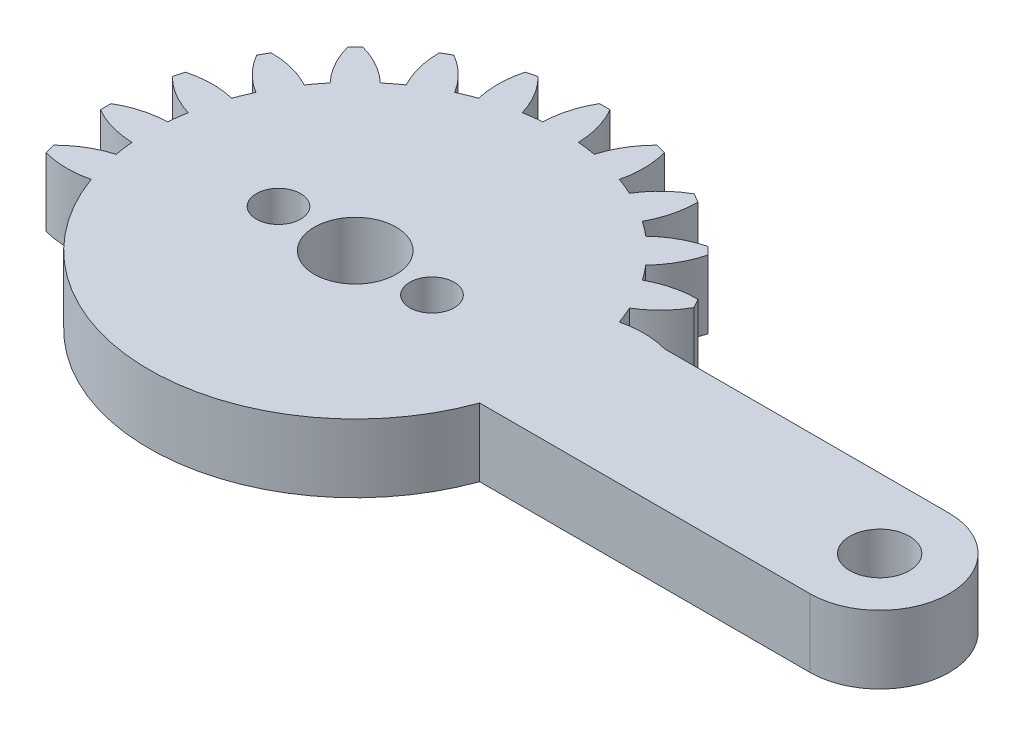
SolidWorks part; units mm, degrees
ref_plane "前视基准面" through (0, 0, 0) normal (0, 0, 1) x (1, 0, 0)
ref_plane "上视基准面" through (0, 0, 0) normal (0, 1, 0) x (1, 0, 0)
ref_plane "右视基准面" through (0, 0, 0) normal (1, 0, 0) x (0, 0, -1)
sketch "草图2" plane through (0, 0, 0) normal (0, 1, 0) x (1, 0, 0)
  line L0 (0, 0) -> (0, 14.63) construction
  line L1 (0, 0) -> (30.75, 0) construction
  line L2 (11.3789, 4.0851) -> (30.75, 4.0851)
  line L3 (30.75, -4.0851) -> (11.3789, -4.0851)
  circle A0 centre (0, 0) radius 14.63
  circle A1 centre (0, 0) radius 12.09
  circle A2 centre (0, 0) radius 1.75
  arc A3 (0.31, 14.6267) -> (1.04, 12.0452) centre (-4.3584, 11.9126) cw
  arc A4 (-0.31, 14.6267) -> (-1.04, 12.0452) centre (4.3584, 11.9126) ccw
  arc A5 (4.0851, 14.0481) -> (4.1221, 11.3656) centre (-1.1267, 12.6347) cw
  arc A6 (3.4862, 14.2086) -> (2.113, 11.9039) centre (7.2931, 10.3787) ccw
  circle A7 centre (0, 0) radius 12.09
  arc A8 (7.5818, 12.5121) -> (6.9233, 9.9114) centre (2.1819, 12.4958) cw
  arc A9 (7.0449, 12.8221) -> (5.1219, 10.9514) centre (9.7308, 8.1374) ccw
  circle A10 centre (0, 0) radius 12.09
  arc A11 (10.5619, 10.1234) -> (9.2526, 7.7818) centre (5.3417, 11.5053) cw
  arc A12 (10.1234, 10.5619) -> (7.7818, 9.2526) centre (11.5053, 5.3417) ccw
  circle A13 centre (0, 0) radius 12.09
  arc A14 (12.8221, 7.0449) -> (10.9514, 5.1219) centre (8.1374, 9.7308) cw
  arc A15 (12.5121, 7.5818) -> (9.9114, 6.9233) centre (12.4958, 2.1819) ccw
  circle A16 centre (0, 0) radius 12.09
  arc A17 (14.2086, 3.4862) -> (11.9039, 2.113) centre (10.3787, 7.2931) cw
  arc A18 (14.0481, 4.0851) -> (11.3656, 4.1221) centre (12.6347, -1.1267) ccw
  circle A19 centre (0, 0) radius 12.09
  arc A20 (14.6267, -0.31) -> (12.0452, -1.04) centre (11.9126, 4.3584) cw
  arc A21 (14.6267, 0.31) -> (12.0452, 1.04) centre (11.9126, -4.3584) ccw
  circle A22 centre (0, 0) radius 12.09
  arc A23 (14.0481, -4.0851) -> (11.3656, -4.1221) centre (12.6347, 1.1267) cw
  arc A24 (14.2086, -3.4862) -> (11.9039, -2.113) centre (10.3787, -7.2931) ccw
  circle A25 centre (0, 0) radius 12.09
  arc A26 (12.5121, -7.5818) -> (9.9114, -6.9233) centre (12.4958, -2.1819) cw
  arc A27 (12.8221, -7.0449) -> (10.9514, -5.1219) centre (8.1374, -9.7308) ccw
  circle A28 centre (0, 0) radius 12.09
  arc A29 (10.1234, -10.5619) -> (7.7818, -9.2526) centre (11.5053, -5.3417) cw
  arc A30 (10.5619, -10.1234) -> (9.2526, -7.7818) centre (5.3417, -11.5053) ccw
  circle A31 centre (0, 0) radius 12.09
  arc A32 (7.0449, -12.8221) -> (5.1219, -10.9514) centre (9.7308, -8.1374) cw
  arc A33 (7.5818, -12.5121) -> (6.9233, -9.9114) centre (2.1819, -12.4958) ccw
  circle A34 centre (0, 0) radius 12.09
  arc A35 (3.4862, -14.2086) -> (2.113, -11.9039) centre (7.2931, -10.3787) cw
  arc A36 (4.0851, -14.0481) -> (4.1221, -11.3656) centre (-1.1267, -12.6347) ccw
  circle A37 centre (0, 0) radius 12.09
  arc A38 (-0.31, -14.6267) -> (-1.04, -12.0452) centre (4.3584, -11.9126) cw
  arc A39 (0.31, -14.6267) -> (1.04, -12.0452) centre (-4.3584, -11.9126) ccw
  circle A40 centre (0, 0) radius 12.09
  arc A41 (-4.0851, -14.0481) -> (-4.1221, -11.3656) centre (1.1267, -12.6347) cw
  arc A42 (-3.4862, -14.2086) -> (-2.113, -11.9039) centre (-7.2931, -10.3787) ccw
  circle A43 centre (0, 0) radius 12.09
  arc A44 (-7.5818, -12.5121) -> (-6.9233, -9.9114) centre (-2.1819, -12.4958) cw
  arc A45 (-7.0449, -12.8221) -> (-5.1219, -10.9514) centre (-9.7308, -8.1374) ccw
  circle A46 centre (0, 0) radius 12.09
  arc A47 (-10.5619, -10.1234) -> (-9.2526, -7.7818) centre (-5.3417, -11.5053) cw
  arc A48 (-10.1234, -10.5619) -> (-7.7818, -9.2526) centre (-11.5053, -5.3417) ccw
  circle A49 centre (0, 0) radius 12.09
  arc A50 (-12.8221, -7.0449) -> (-10.9514, -5.1219) centre (-8.1374, -9.7308) cw
  arc A51 (-12.5121, -7.5818) -> (-9.9114, -6.9233) centre (-12.4958, -2.1819) ccw
  circle A52 centre (0, 0) radius 12.09
  arc A53 (-14.2086, -3.4862) -> (-11.9039, -2.113) centre (-10.3787, -7.2931) cw
  arc A54 (-14.0481, -4.0851) -> (-11.3656, -4.1221) centre (-12.6347, 1.1267) ccw
  circle A55 centre (0, 0) radius 12.09
  arc A56 (-14.6267, 0.31) -> (-12.0452, 1.04) centre (-11.9126, -4.3584) cw
  arc A57 (-14.6267, -0.31) -> (-12.0452, -1.04) centre (-11.9126, 4.3584) ccw
  circle A58 centre (0, 0) radius 12.09
  arc A59 (-14.0481, 4.0851) -> (-11.3656, 4.1221) centre (-12.6347, -1.1267) cw
  arc A60 (-14.2086, 3.4862) -> (-11.9039, 2.113) centre (-10.3787, 7.2931) ccw
  circle A61 centre (0, 0) radius 12.09
  arc A62 (-12.5121, 7.5818) -> (-9.9114, 6.9233) centre (-12.4958, 2.1819) cw
  arc A63 (-12.8221, 7.0449) -> (-10.9514, 5.1219) centre (-8.1374, 9.7308) ccw
  circle A64 centre (0, 0) radius 12.09
  arc A65 (-10.1234, 10.5619) -> (-7.7818, 9.2526) centre (-11.5053, 5.3417) cw
  arc A66 (-10.5619, 10.1234) -> (-9.2526, 7.7818) centre (-5.3417, 11.5053) ccw
  circle A67 centre (0, 0) radius 12.09
  arc A68 (-7.0449, 12.8221) -> (-5.1219, 10.9514) centre (-9.7308, 8.1374) cw
  arc A69 (-7.5818, 12.5121) -> (-6.9233, 9.9114) centre (-2.1819, 12.4958) ccw
  circle A70 centre (0, 0) radius 12.09
  arc A71 (-3.4862, 14.2086) -> (-2.113, 11.9039) centre (-7.2931, 10.3787) cw
  arc A72 (-4.0851, 14.0481) -> (-4.1221, 11.3656) centre (1.1267, 12.6347) ccw
  circle A73 centre (0, 0) radius 12.09
  arc A74 (30.75, 4.0851) -> (30.75, -4.0851) centre (30.75, 0) cw
  circle A75 centre (30.75, 0) radius 1.75
  point P175 (0, 0)
  dimension "D1" = 3.5
  dimension "D2" = 24.18
  dimension "D3" = 29.26
  dimension "D6" = 5.4
  dimension "D9" = 3.5
  dimension "D10" = 4.0851
  dimension "D4" = 0.62
  dimension "D5" = 2.08
  dimension "D8" = 30.75
  dimension "D7" = 24
extrude "凸台-拉伸1" add sketch "草图2" along normal blind 4 contours A74 L2 A0 L3 A75 | A17 A0 L2 A16 | L2 A18 A1 | A21 A0 A17 A1 | A0 A21 A19 A20 | A24 A0 A20 A22 | A0 A24 A1 L3 | A0 A15 A13 A14 | A0 A12 A10 A11 | A0 A9 A7 A8 | A1 A16 A13 A10 A7 A70 A67 A64 A61 A58 A55 A52 A49 A46 A43 A40 A37 A34 A31 A28 A25 A22 A19 | A0 A6 A1 A5 | A0 A4 A1 A3 | A0 A72 A70 A71 | A0 A69 A67 A68 | A0 A66 A64 A65 | A0 A63 A61 A62 | A0 A60 A58 A59 | A0 A57 A55 A56 | A0 A54 A52 A53
sketch "草图3" plane through (0, 4, 0) normal (0, 1, 0) x (1, 0, 0)
  line L0 (-4.5, 0) -> (4.5, 0) construction
  circle A0 centre (0, 0) radius 2.4
  circle A1 centre (4.5, 0) radius 1.3
  circle A2 centre (-4.5, 0) radius 1.3
  point P8 (0, 0)
  dimension "D1" = 4.8
  dimension "D2" = 2.6
  dimension "D3" = 2.6
  dimension "D4" = 9
extrude "切除-拉伸1" cut sketch "草图3" against normal through all
